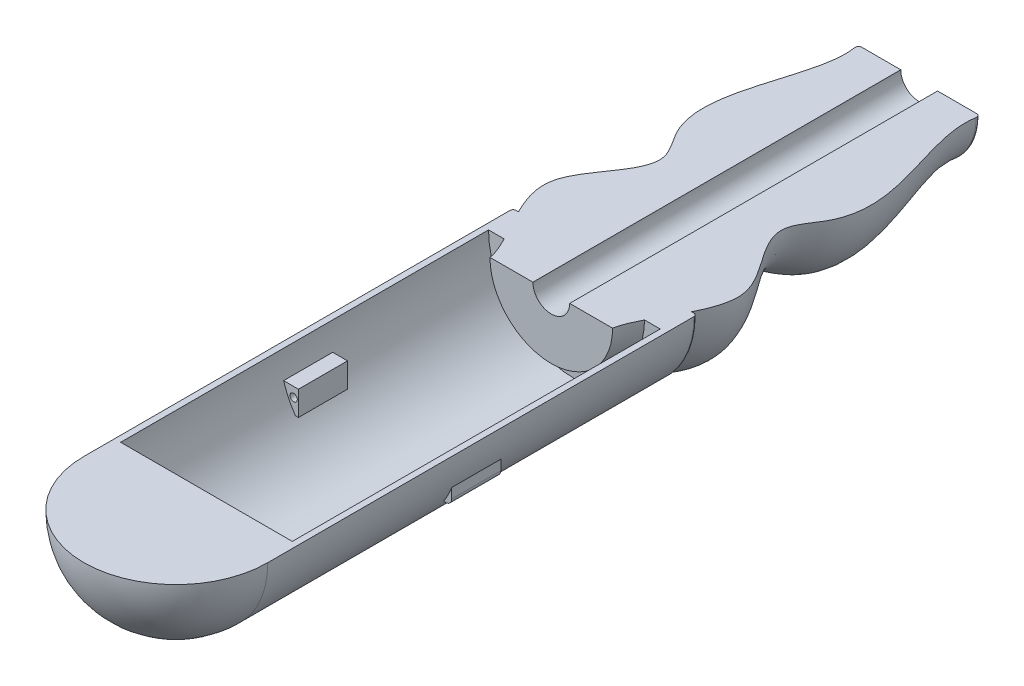
SolidWorks part; units mm, degrees
ref_plane "Front Plane" through (0, 0, 0) normal (0, 0, 1) x (1, 0, 0)
ref_plane "Top Plane" through (0, 0, 0) normal (0, 1, 0) x (1, 0, 0)
ref_plane "Right Plane" through (0, 0, 0) normal (1, 0, 0) x (0, 0, -1)
sketch "Sketch1" plane through (0, 0, 0) normal (0, 0, 1) x (1, 0, 0)
  circle A0 centre (0, 0) radius 38.1
extrude "Boss-Extrude1" add sketch "Sketch1" along normal blind 177.8
sketch "Sketch2" plane through (0, 0, 177.8) normal (0, 0, 1) x (1, 0, 0)
  line L0 (0, 38.1) -> (0, -38.1)
  arc A0 (0, 38.1) -> (0, -38.1) centre (0, 0) ccw
revolve "Revolve1" add sketch "Sketch2" angle 360 about L0
ref_plane "Plane1" through (0, 0, 12.7) normal (0, 0, -1) x (-1, 0, 0)
sketch "Sketch3" plane through (0, 0, 12.7) normal (0, 0, -1) x (-1, 0, 0)
  circle A0 centre (0, 0) radius 35.56
extrude "Cut-Extrude1" cut sketch "Sketch3" against normal blind 152.4
sketch "Sketch5" plane through (0, 0, 12.7) normal (0, 0, -1) x (-1, 0, 0)
  line L0 (-85.6058, 0) -> (76.2912, 0)
  line L1 (76.2912, 50.1752) -> (-83.9334, 50.1752)
  line L2 (76.2912, 50.1752) -> (76.2912, -68.2878)
  line L3 (76.2912, -68.2878) -> (-83.9334, -68.2878)
  line L4 (-83.9334, 50.1752) -> (-83.9334, -68.2878)
ref_plane "Plane2" through (0, 0, 0) normal (0, -1, 0) x (-1, 0, 0)
sketch "Sketch6" plane through (0, 0, 0) normal (0, -1, 0) x (-1, 0, 0)
  line L0 (0, -22.266) -> (0, 130.134)
  line L1 (0, -22.266) -> (-25.4, -22.266)
  line L3 (0, 130.134) -> (-25.4, 130.134)
  spline S0 degree 3 poles (-25.4, -22.266) (-27.2095, -11.4359) (-47.2653, 9.6985) (-32.8782, 32.2092) (-21.126, 47.8683) (-46.9743, 77.0991) (-20.8842, 111.2446) (-25.4, 130.134) knots 0 0 0 0 0.261327 0.359607 0.483525 0.565956 1 1 1 1
revolve "Revolve2" add sketch "Sketch6" angle 360 about L0
fillet "Fillet2" radius 1.27 1 edges at (38.1, 0, 0)
fillet "Fillet3" radius 1.27 1 edges at (25.4, 0, -130.134)
sketch "Sketch8" plane through (0, 0, 0) normal (0, -1, 0) x (-1, 0, 0)
  line L1 (85.3466, -225.5421) -> (-77.2366, -225.5421)
  line L2 (85.3466, -225.5421) -> (85.3466, 157.3897)
  line L3 (85.3466, 157.3897) -> (-77.2366, 157.3897)
  line L4 (-77.2366, -225.5421) -> (-77.2366, 157.3897)
sketch "Sketch9" plane through (0, 0, -130.134) normal (0, 0, -1) x (-1, 0, 0)
  circle A0 centre (0, 0) radius 7.62
extrude "Cut-Extrude2" cut sketch "Sketch9" against normal blind 165.1 contours A0
extrude "Cut-Extrude3" cut sketch "Sketch8" against normal blind 76.2 contours L2 L3 L4 L1
ref_plane "Plane3" through (-35.56, 0, 0) normal (1, 0, 0) x (0, 0, -1)
sketch "Sketch13" plane through (-35.56, 0, 0) normal (1, 0, 0) x (0, 0, -1)
  line L0 (-165.1, 0) -> (-88.9, 0) construction
  line L1 (-165.1, 0) -> (-12.7, 0) construction
  line L2 (-88.9, 0) -> (-88.9, -10.16) construction
  line L3 (-88.9, -10.16) -> (-99.06, -10.16)
  line L4 (-99.06, -10.16) -> (-99.06, -20.32)
  line L5 (-99.06, -20.32) -> (-78.74, -20.32)
  line L6 (-78.74, -20.32) -> (-78.74, -10.16)
  line L7 (-78.74, -10.16) -> (-88.9, -10.16)
extrude "Boss-Extrude2" add sketch "Sketch13" along normal blind 7.62
sketch "Sketch14" plane through (0, 0, 78.74) normal (0, 0, -1) x (-1, 0, 0)
  circle A0 centre (29.946, -14.1636) radius 1.524
extrude "Cut-Extrude4" cut sketch "Sketch14" against normal blind 22.86
fillet "Fillet5" radius 2.54 1 edges at (-35.56, -20.32, 88.9)
ref_plane "Plane4" through (35.56, 0, 0) normal (-1, 0, 0) x (0, 0, 1)
sketch "Sketch15" plane through (35.56, 0, 0) normal (-1, 0, 0) x (0, 0, 1)
  line L0 (165.1, 0) -> (88.9, 0) construction
  line L1 (12.7, 0) -> (165.1, 0) construction
  line L2 (88.9, 0) -> (88.9, -10.16) construction
  line L3 (88.9, -10.16) -> (78.74, -10.16)
  line L4 (78.74, -10.16) -> (78.74, -20.32)
  line L5 (78.74, -20.32) -> (99.06, -20.32)
  line L6 (99.06, -20.32) -> (99.06, -10.16)
  line L7 (99.06, -10.16) -> (88.9, -10.16)
extrude "Boss-Extrude3" add sketch "Sketch15" along normal blind 7.62
fillet "Fillet6" radius 2.54 1 edges at (35.56, -20.32, 88.9)
sketch "Sketch16" plane through (0, 0, 78.74) normal (0, 0, -1) x (-1, 0, 0)
  circle A0 centre (-30.3326, -13.542) radius 1.524
extrude "Cut-Extrude5" cut sketch "Sketch16" against normal blind 22.86 contours A0
